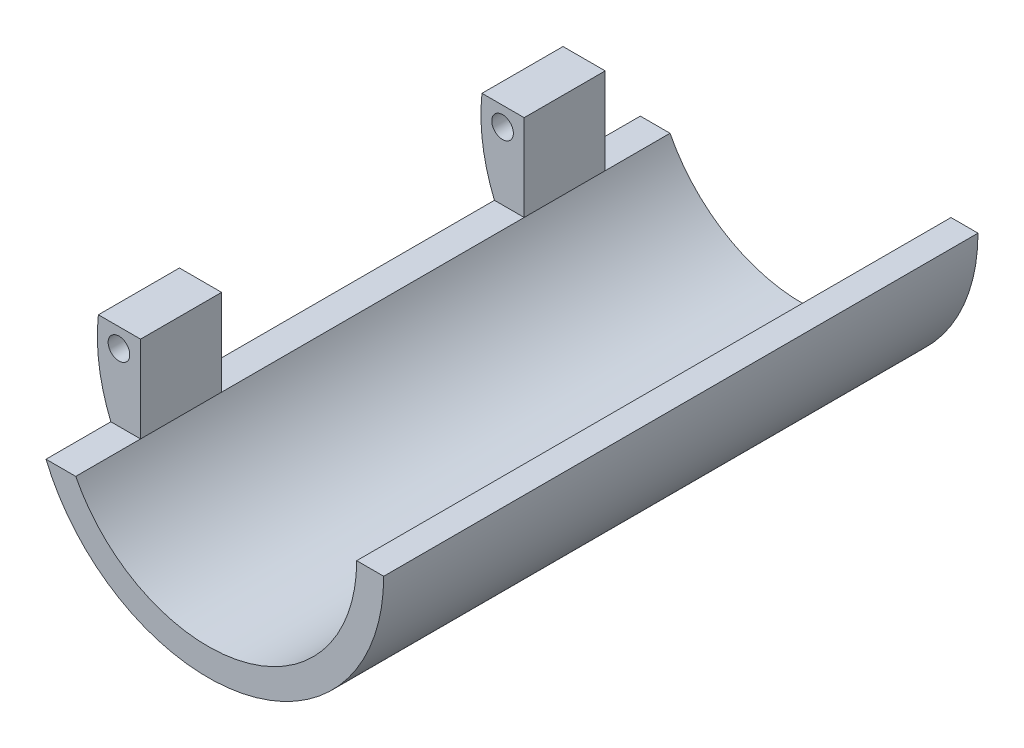
SolidWorks part; units mm, degrees
ref_plane "Alzado" through (0, 0, 0) normal (0, 0, 1) x (1, 0, 0)
ref_plane "Planta" through (0, 0, 0) normal (0, 1, 0) x (1, 0, 0)
ref_plane "Vista lateral" through (0, 0, 0) normal (1, 0, 0) x (0, 0, -1)
sketch "Croquis2" plane through (0, 0, 0) normal (0, 0, 1) x (1, 0, 0)
  line L0 (0, 0) -> (27.5, 0) construction
  line L1 (27.5, 0) -> (32.5, 0)
  line L2 (-24.5, 3.51) -> (-24.5, -12.49)
  line L4 (-24.5, 3.51) -> (-32.3099, 3.51)
  line L5 (0, 0) -> (-24.5, 0) construction
  line L6 (-24.5, 0) -> (-32.5, 0) construction
  arc A0 (-32.3099, 3.51) -> (32.5, 0) centre (0, 0) ccw
  arc A1 (-24.5, -12.49) -> (27.5, 0) centre (0, 0) ccw
  circle A2 centre (-28.5, 0) radius 2
  dimension "D1" = 65
  dimension "D2" = 5
  dimension "D5" = 4
  dimension "D3" = 24.5
  dimension "D4" = 16
extrude "ParedMovil" add sketch "Croquis2" along normal blind 110
sketch "Croquis3" plane through (-24.5, 0, 0) normal (1, 0, 0) x (0, 0, -1)
  line L0 (-98, 3.51) -> (-98, -12.49)
  line L1 (-110, 3.51) -> (0, 3.51) construction
  line L2 (-98, -12.49) -> (-110, -12.49)
  line L3 (-110, -12.49) -> (-110, 3.51) construction
  line L4 (-98, 3.51) -> (-110, 3.51)
  line L5 (-110, 3.51) -> (-110, -12.49)
  line L6 (-110, 3.51) -> (0, 3.51) construction
  line L7 (-55, 3.51) -> (-55, -7.673) construction
  line L8 (0, 3.51) -> (0, -12.49)
  line L9 (-12, 3.51) -> (0, 3.51)
  line L10 (-12, -12.49) -> (0, -12.49)
  line L11 (-12, 3.51) -> (-12, -12.49)
  line L12 (-83, 3.51) -> (-27, 3.51)
  line L13 (-83, 3.51) -> (-83, -12.49)
  line L14 (-110, -12.49) -> (0, -12.49) construction
  line L15 (-83, -12.49) -> (-27, -12.49)
  line L16 (-27, 3.51) -> (-27, -12.49)
  point P22 (-55, -12.49)
  dimension "D1" = 16
  dimension "D2" = 12
  dimension "D3" = 15
extrude "Visagra" cut sketch "Croquis3" against normal up to next
